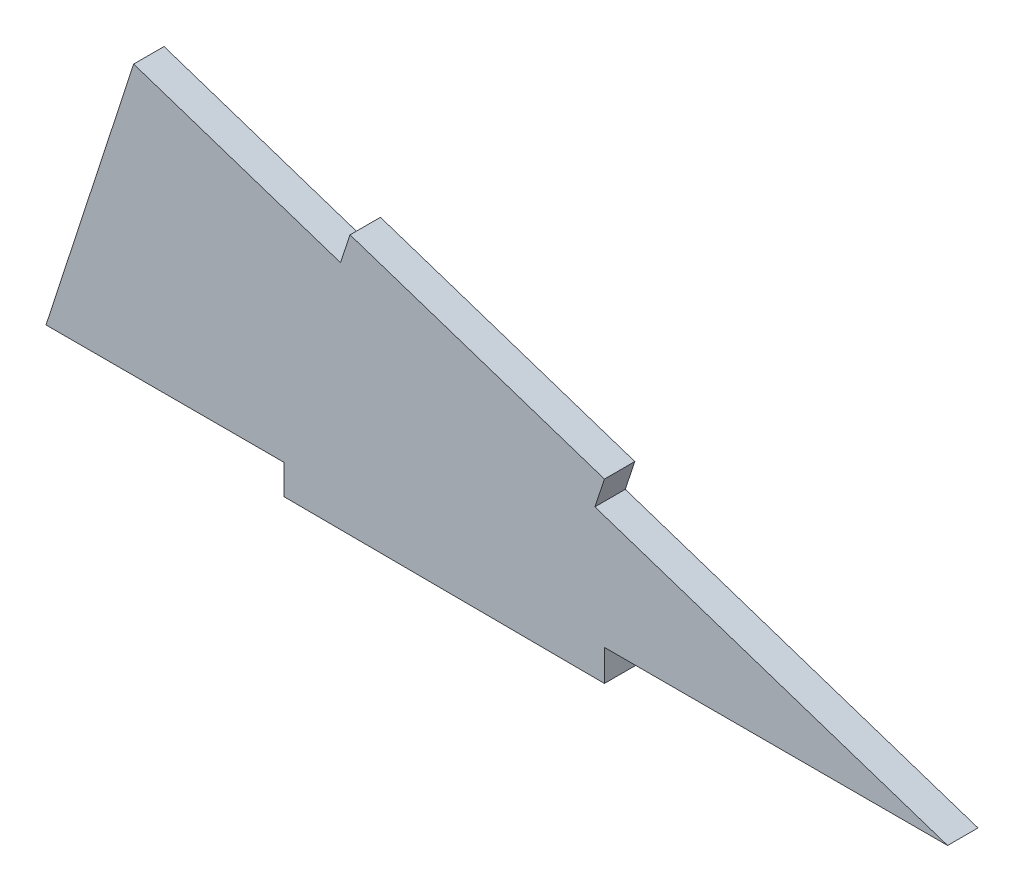
SolidWorks part; units mm, degrees
ref_plane "Front Plane" through (0, 0, 0) normal (0, 0, 1) x (1, 0, 0)
ref_plane "Top Plane" through (0, 0, 0) normal (0, 1, 0) x (1, 0, 0)
ref_plane "Right Plane" through (0, 0, 0) normal (1, 0, 0) x (0, 0, -1)
sketch "Sketch1" plane through (0, 0, 0) normal (0, 0, 1) x (1, 0, 0)
  line L0 (0, 0) -> (-89, 0)
  line L2 (-80.3475, 26.6296) -> (0, 0)
  line L3 (-89, 0) -> (-80.3475, 26.6296)
  dimension "D1" = 89
  dimension "D2" = 28
  dimension "D3" = 72
extrude "Boss-Extrude1" add sketch "Sketch1" along normal blind 3
sketch "Sketch2" plane through (0, 0, 3) normal (0, 0, 1) x (1, 0, 0)
sketch "Sketch3" plane through (0, 0, 3) normal (0, 0, 1) x (1, 0, 0)
  line L0 (-65.5272, 0) -> (-65.5272, -2.9339)
  line L1 (-89, 0) -> (0, 0) construction
  line L2 (-65.5272, -2.9339) -> (-33.8743, -3.0872)
  line L3 (-33.8743, -3.0872) -> (-33.8743, 0)
  line L4 (-33.8743, 0) -> (-65.5272, 0)
  line L5 (-59.9311, 19.863) -> (-58.9873, 22.7106)
  line L6 (0, 0) -> (-80.3475, 26.6296) construction
  line L7 (-58.9873, 22.7106) -> (-33.8743, 14.3875)
  line L8 (-33.8743, 14.3875) -> (-34.8181, 11.5398)
  line L9 (-34.8181, 11.5398) -> (-59.9311, 19.863)
extrude "Boss-Extrude2" add sketch "Sketch3" against normal blind 3
